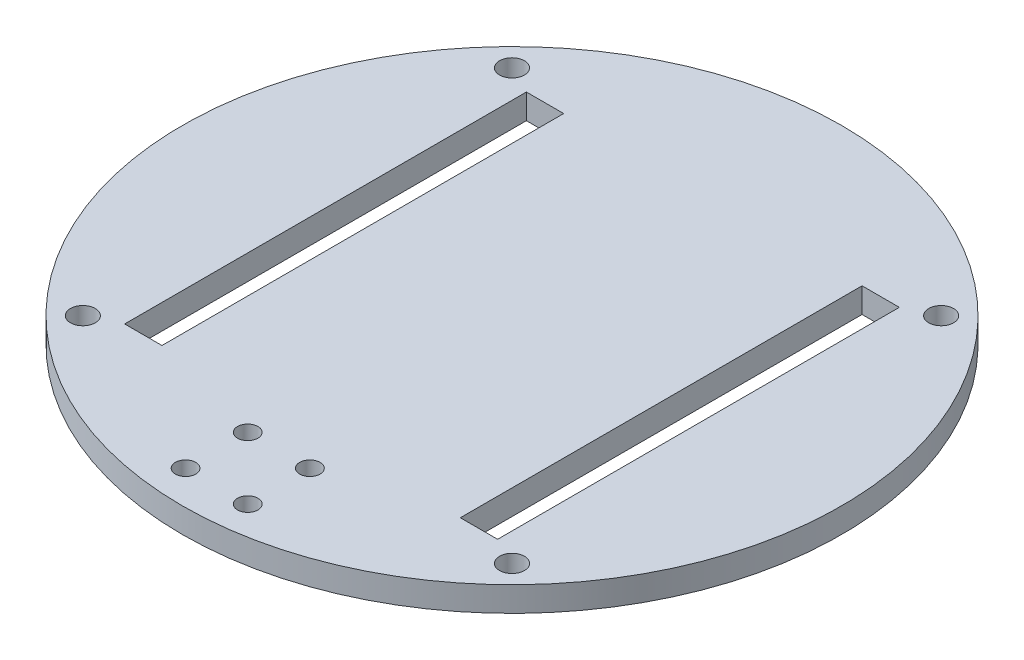
SolidWorks part; units mm, degrees
ref_plane "Front Plane" through (0, 0, 0) normal (0, 0, 1) x (1, 0, 0)
ref_plane "Top Plane" through (0, 0, 0) normal (0, 1, 0) x (1, 0, 0)
ref_plane "Right Plane" through (0, 0, 0) normal (1, 0, 0) x (0, 0, -1)
sketch "Sketch1" plane through (0, 66.8, 0) normal (0, 1, 0) x (1, 0, 0)
  line L0 (-38.1, -51.3017) -> (-47.625, -51.3017)
  line L8 (0, 0) -> (-54.8008, 54.8008) construction
  line L21 (-38.1, -51.3017) -> (-47.625, -51.3017)
  line L22 (-47.625, 51.3017) -> (-38.1, 51.3017)
  line L23 (-47.625, 51.3017) -> (-38.1, 51.3017)
  line L24 (38.1, 51.3017) -> (47.625, 51.3017)
  line L25 (38.1, 51.3017) -> (47.625, 51.3017)
  line L26 (47.625, -51.3017) -> (38.1, -51.3017)
  line L27 (47.625, -51.3017) -> (38.1, -51.3017)
  line L28 (-47.625, 51.3017) -> (-47.625, -51.3017)
  line L29 (-38.1, 51.3017) -> (-38.1, -51.3017)
  line L30 (38.1, 51.3017) -> (38.1, -51.3017)
  line L31 (47.625, 51.3017) -> (47.625, -51.3017)
  circle A0 centre (0, 0) radius 70 construction
  circle A1 centre (0, 0) radius 84.1675 construction
  circle A4 centre (-54.8008, 54.8008) radius 3.175 construction
  circle A5 centre (-54.8008, 54.8008) radius 3.175
  circle A6 centre (54.8008, 54.8008) radius 3.175
  circle A7 centre (54.8008, -54.8008) radius 3.175
  circle A8 centre (-54.8008, -54.8008) radius 3.175
  circle A9 centre (0, 0) radius 70
  circle A10 centre (0, 0) radius 84.1675
  circle A11 centre (7.9375, -75.4317) radius 3.175 construction
  circle A13 centre (-54.8008, 54.8008) radius 3.175 construction
  circle A23 centre (7.9375, -59.5567) radius 3.175 construction
  circle A24 centre (-7.9375, -59.5567) radius 3.175 construction
  circle A25 centre (-7.9375, -75.4317) radius 3.175 construction
  circle A26 centre (7.9375, -75.4317) radius 3.175 construction
  circle A27 centre (7.9375, -59.5567) radius 3.175 construction
  circle A28 centre (-7.9375, -59.5567) radius 3.175 construction
  circle A29 centre (-7.9375, -75.4317) radius 3.175 construction
  circle A30 centre (7.9375, -75.4317) radius 2.6035
  circle A31 centre (-7.9375, -75.4317) radius 2.6035
  circle A32 centre (-7.9375, -59.5567) radius 2.6035
  circle A33 centre (7.9375, -59.5567) radius 2.6035
  point P18 (0, 0)
  dimension "D1" = 5.207
  dimension "D2" = 4
extrude "Boss-Extrude1" add sketch "Sketch1" along normal blind 6.35
ref_plane "Plane1" through (0, 69.975, 0) normal (0, 1, 0) x (1, 0, 0)
